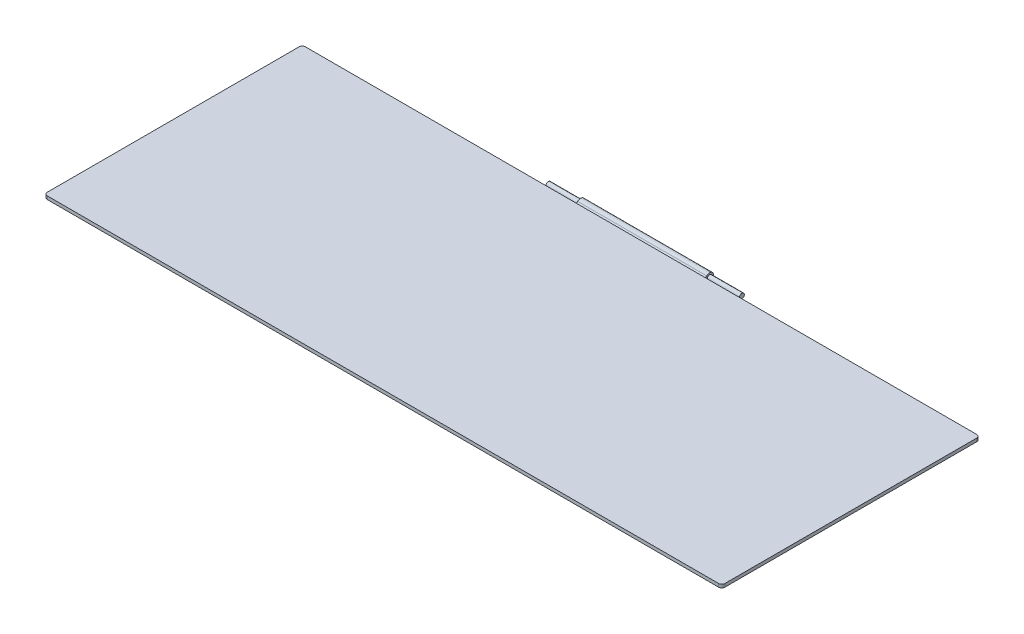
SolidWorks part; units mm, degrees
ref_plane "Front Plane" through (0, 0, 0) normal (0, 0, 1) x (1, 0, 0)
ref_plane "Top Plane" through (0, 0, 0) normal (0, 1, 0) x (1, 0, 0)
ref_plane "Right Plane" through (0, 0, 0) normal (1, 0, 0) x (0, 0, -1)
sketch "Sketch1" plane through (0, 0, 0) normal (0, 0, 1) x (1, 0, 0)
  line L1 (266.7, 1.27) -> (-266.7, 1.27)
  line L2 (266.7, 1.27) -> (266.7, -1.27)
  line L3 (266.7, -1.27) -> (-266.7, -1.27)
  line L4 (-266.7, 1.27) -> (-266.7, -1.27)
  line L5 (266.7, 1.27) -> (-266.7, -1.27) construction
  line L6 (266.7, -1.27) -> (-266.7, 1.27) construction
  point P0 (0, 0)
  dimension "D1" = 2.54
  dimension "D2" = 533.4
extrude "Boss-Extrude1" add sketch "Sketch1" along normal blind 203.2 contours L1 L4 L3 L2
fillet "Fillet1" radius 2.54 4 edges at (-266.7, 0, 0) (266.7, 0, 0) (266.7, 0, 203.2) (-266.7, 0, 203.2)
ref_plane "Plane1" through (-50.8, 0, 0) normal (-1, 0, 0) x (0, 0, 1)
sketch "Sketch3" plane through (-50.8, 0, 0) normal (-1, 0, 0) x (0, 0, 1)
  line L0 (0, -1.27) -> (0, 1.27) construction
  line L1 (0, -1.27) -> (0, 1.27)
  line L2 (0, 1.27) -> (-0.8759, 2.1897)
  line L3 (0, -1.27) -> (-0.8759, -2.1897)
  circle A0 centre (-3.175, 0) radius 3.175
  point P6 (0, 0)
  point P8 (0, 0)
  dimension "D1" = 6.35
extrude "Boss-Extrude2" add sketch "Sketch3" against normal blind 101.6 contours A0 L1 L2 | A0 L3 L1 | A0
sketch "Sketch5" plane through (-50.8, 0, 0) normal (-1, 0, 0) x (0, 0, 1)
  circle A0 centre (-3.175, 0) radius 1.905
  dimension "D1" = 3.81
extrude "Boss-Extrude3" add sketch "Sketch5" along normal blind 25.4
sketch "Sketch6" plane through (50.8, 0, 0) normal (1, 0, 0) x (0, 0, -1)
  circle A0 centre (3.175, 0) radius 1.905
  dimension "D1" = 3.81
extrude "Boss-Extrude4" add sketch "Sketch6" along normal blind 25.4
